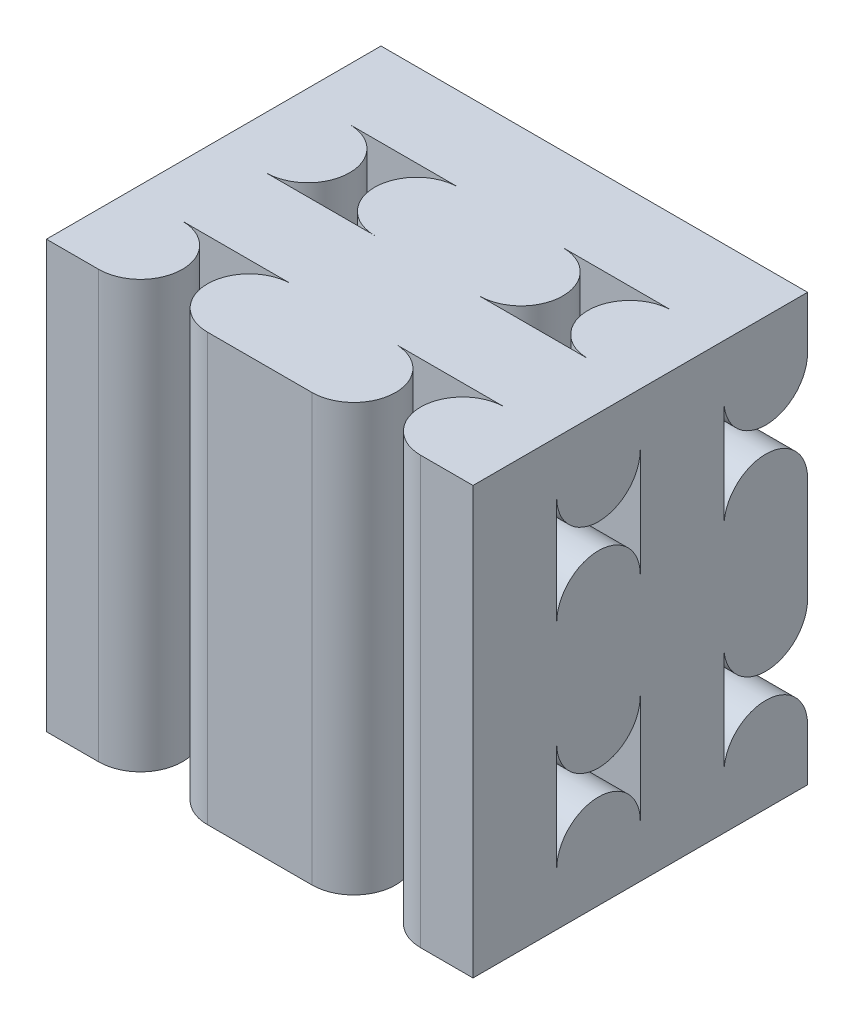
SolidWorks part; units mm, degrees
ref_plane "Płaszczyzna przednia" through (0, 0, 0) normal (0, 0, 1) x (1, 0, 0)
ref_plane "Płaszczyzna górna" through (0, 0, 0) normal (0, 1, 0) x (1, 0, 0)
ref_plane "Płaszczyzna prawa" through (0, 0, 0) normal (1, 0, 0) x (0, 0, -1)
sketch "Szkic1" plane through (0, 0, 0) normal (0, 1, 0) x (1, 0, 0)
  line L0 (-0.255, 0) -> (-0.13, 0)
  line L1 (-0.13, 0.2) -> (-0.255, 0.2)
  line L2 (-0.255, 0.2) -> (-0.255, 0)
  line L3 (0, -0.33) -> (0, 0.33) construction
  line L4 (0.13, 0.2) -> (0.38, 0.2)
  line L5 (0.38, 0) -> (0.13, 0)
  line L6 (0.255, 0.2) -> (0.255, 0)
  line L7 (0.64, 0.2) -> (0.765, 0.2)
  line L8 (0.765, 0) -> (0.64, 0)
  line L9 (0.765, 0.2) -> (0.765, 0)
  line L10 (-0.255, 0.6) -> (-0.255, 0.4)
  line L11 (-0.255, 0.4) -> (-0.13, 0.4)
  line L12 (-0.13, 0.6) -> (-0.255, 0.6)
  line L13 (0.255, 0.6) -> (0.255, 0.4)
  line L14 (0.13, 0.6) -> (0.38, 0.6)
  line L15 (0.38, 0.4) -> (0.13, 0.4)
  line L16 (0.64, 0.6) -> (0.765, 0.6)
  line L17 (0.765, 0.6) -> (0.765, 0.4)
  line L18 (0.765, 0.4) -> (0.64, 0.4)
  arc A0 (-0.13, 0) -> (-0.13, 0.2) centre (-0.13, 0.1) ccw
  arc A1 (0.13, 0) -> (0.13, 0.2) centre (0.13, 0.1) cw
  arc A2 (0.38, 0) -> (0.38, 0.2) centre (0.38, 0.1) ccw
  arc A3 (0.64, 0) -> (0.64, 0.2) centre (0.64, 0.1) cw
  arc A4 (-0.13, 0.4) -> (-0.13, 0.6) centre (-0.13, 0.5) ccw
  arc A5 (0.38, 0.4) -> (0.38, 0.6) centre (0.38, 0.5) ccw
  arc A6 (0.13, 0.4) -> (0.13, 0.6) centre (0.13, 0.5) cw
  arc A7 (0.64, 0.4) -> (0.64, 0.6) centre (0.64, 0.5) cw
  point P5 (-0.03, 0.1)
  dimension "D1" = 0.2
  dimension "D2" = 0.225
  dimension "D3" = 0.51
  dimension "D5" = 0.2
  dimension "D4" = 2
extrude "Dodanie-wyciągnięcie1" add sketch "Szkic1" along normal blind 1.02 contours L0 A0 L1 L2 | L11 A4 L12 L10 | A6 L15 L13 L14 | L15 A5 L14 L13 | L5 A2 L4 L6 | A1 L5 L6 L4 | A3 L8 L9 L7 | A7 L18 L17 L16
sketch "Szkic4" plane through (0, 0, 0) normal (1, 0, 0) x (0, 0, -1)
  line L0 (0.2, 1.02) -> (0.2, 0.895)
  line L1 (0.2, 1.02) -> (0.2, 0) construction
  line L2 (0.4, 1.02) -> (0.4, 0) construction
  line L3 (0.4, 0.895) -> (0.4, 1.02)
  line L4 (0.4, 1.02) -> (0.2, 1.02)
  line L5 (0.2, 0.51) -> (0.4, 0.51)
  line L6 (0.4, 0.385) -> (0.4, 0.635)
  line L7 (0.2, 0.635) -> (0.2, 0.385)
  line L8 (0.4, 0.125) -> (0.4, 0)
  line L9 (0.2, 0) -> (0.2, 0.125)
  line L10 (0.4, 0) -> (0.2, 0)
  line L11 (0.8, 1.02) -> (0.6, 1.02)
  line L12 (0.6, 1.02) -> (0.6, 0.895)
  line L13 (0.8, 0.895) -> (0.8, 1.02)
  line L14 (0.8, 0.125) -> (0.8, 0)
  line L15 (0.8, 0) -> (0.6, 0)
  line L16 (0.6, 0) -> (0.6, 0.125)
  line L17 (0.6, 0.635) -> (0.6, 0.385)
  line L18 (0.6, 0.51) -> (0.8, 0.51)
  line L19 (0.8, 0.385) -> (0.8, 0.635)
  arc A0 (0.2, 0.895) -> (0.4, 0.895) centre (0.3, 0.895) ccw
  arc A1 (0.4, 0.635) -> (0.2, 0.635) centre (0.3, 0.635) ccw
  arc A2 (0.2, 0.125) -> (0.4, 0.125) centre (0.3, 0.125) cw
  arc A3 (0.4, 0.385) -> (0.2, 0.385) centre (0.3, 0.385) cw
  arc A4 (0.6, 0.895) -> (0.8, 0.895) centre (0.7, 0.895) ccw
  arc A5 (0.6, 0.125) -> (0.8, 0.125) centre (0.7, 0.125) cw
  arc A6 (0.8, 0.385) -> (0.6, 0.385) centre (0.7, 0.385) cw
  arc A7 (0.8, 0.635) -> (0.6, 0.635) centre (0.7, 0.635) ccw
  point P9 (0.3, 0.795)
  point P17 (0.3, 0.735)
  dimension "D1" = 0.225
  dimension "D2" = 0.225
  dimension "D4" = 0.2
  dimension "D3" = 2
extrude "Dodanie-wyciągnięcie2" add sketch "Szkic4" along normal blind 1.02 from surface at -0.255 contours L12 A4 L13 L11 | L19 A7 L17 L18 | A6 L19 L18 L17 | A5 L16 L15 L14 | A2 L9 L10 L8 | A3 L6 L5 L7 | L6 A1 L7 L5 | L0 A0 L3 L4 starting at face at (-0.255, 0.51, -0.1)
